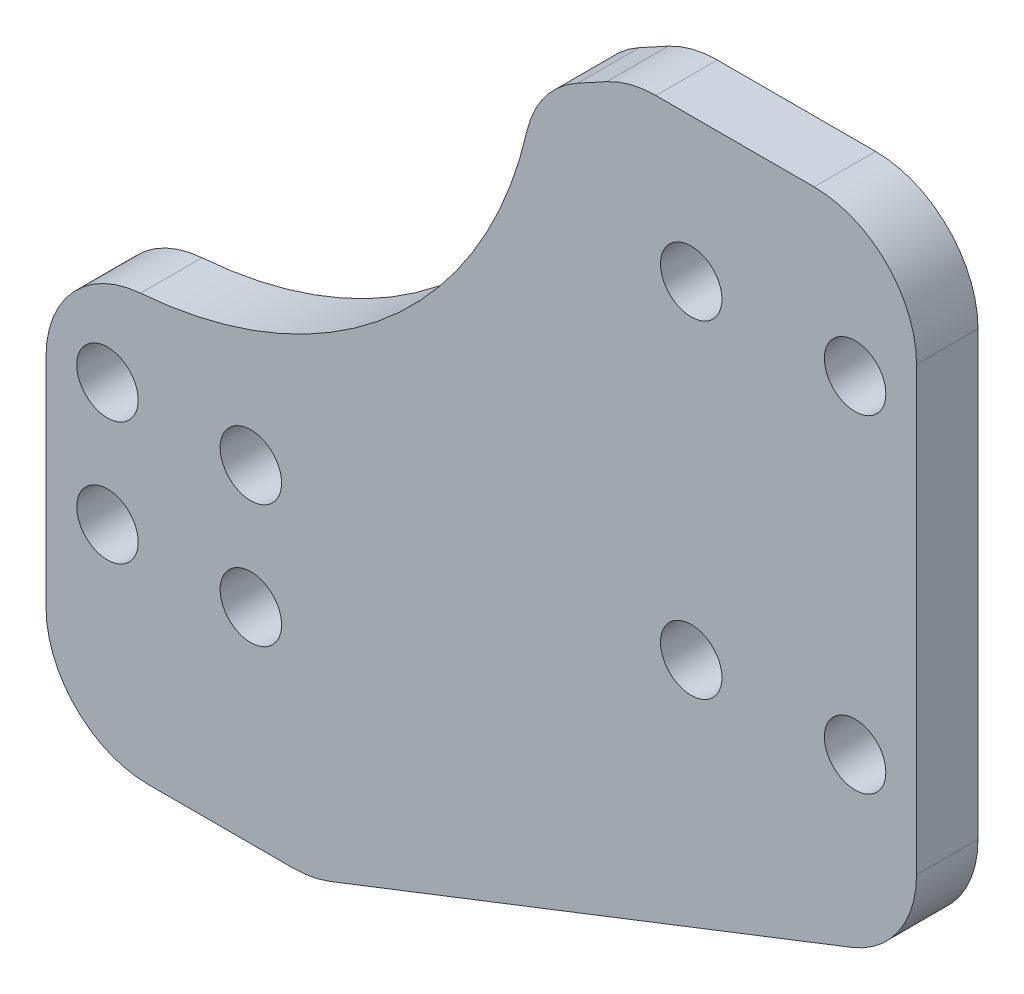
SolidWorks part; units mm, degrees
material "Thornel Mat VMA"
ref_plane "前视基准面" through (0, 0, 0) normal (0, 0, 1) x (1, 0, 0)
ref_plane "上视基准面" through (0, 0, 0) normal (0, 1, 0) x (1, 0, 0)
ref_plane "右视基准面" through (0, 0, 0) normal (1, 0, 0) x (0, 0, -1)
other "Configuration Table"
sketch "草图1" plane through (0, 0, 0) normal (0, 0, 1) x (1, 0, 0)
  line L0 (36, -1.48) -> (6.5, -13)
  line L1 (-6.5, -13) -> (6.5, -13)
  line L2 (-6.5, -13) -> (-6.5, 13)
  line L3 (-6.5, 13) -> (6.5, 13)
  line L4 (6.5, -13) -> (6.5, 13)
  line L5 (-6.5, -13) -> (6.5, 13) construction
  line L6 (-6.5, 13) -> (6.5, -13) construction
  line L7 (-3.5, -3) -> (3.5, -3) construction
  line L8 (-3.5, -3) -> (-3.5, 3) construction
  line L9 (-3.5, 3) -> (3.5, 3) construction
  line L10 (3.5, -3) -> (3.5, 3) construction
  line L11 (-3.5, -3) -> (3.5, 3) construction
  line L12 (-3.5, 3) -> (3.5, -3) construction
  line L13 (22, 28.52) -> (36, 28.52)
  line L14 (22, 28.52) -> (22, -1.48)
  line L15 (22, -1.48) -> (36, -1.48)
  line L16 (36, 28.52) -> (36, -1.48)
  line L17 (22, 28.52) -> (36, -1.48) construction
  line L18 (22, -1.48) -> (36, 28.52) construction
  line L19 (25, 5.52) -> (33, 5.52) construction
  line L20 (25, 5.52) -> (25, 21.52) construction
  line L21 (25, 21.52) -> (33, 21.52) construction
  line L22 (33, 5.52) -> (33, 21.52) construction
  line L23 (25, 5.52) -> (33, 21.52) construction
  line L24 (25, 21.52) -> (33, 5.52) construction
  line L25 (22, 28.52) -> (-6.5, 13)
  circle A0 centre (33, 21.52) radius 1.5
  circle A1 centre (33, 5.52) radius 1.5
  circle A2 centre (25, 5.52) radius 1.5
  circle A3 centre (25, 21.52) radius 1.5
  circle A4 centre (3.5, 3) radius 1.5
  circle A5 centre (3.5, -3) radius 1.5
  circle A6 centre (-3.5, -3) radius 1.5
  circle A7 centre (-3.5, 3) radius 1.5
  point P0 (0, 0)
  point P6 (0, 0)
  point P11 (29, 13.52)
  point P16 (29, 13.52)
  dimension "D1" = 3
  dimension "D9" = 10
  dimension "D10" = 3
  dimension "D2" = 8
  dimension "D3" = 29
  dimension "D4" = 13.52
  dimension "D5" = 3
  dimension "D6" = 30
  dimension "D7" = 7
  dimension "D8" = 6
  dimension "D11" = 16
extrude "凸台-拉伸1" add sketch "草图1" along normal blind 3 contours L1 L4 L3 L2 A7 A6 A5 A4 | L14 L25 L3 L4 L0 L15 | L16 L13 L14 L15 A3 A2 A1 A0
sketch "草图2" plane through (0, 0, 3) normal (0, 0, 1) x (1, 0, 0)
  line L0 (-6.5, -13) -> (-6.5, 13) construction
  line L2 (22, 28.52) -> (36, 28.52) construction
  circle A0 centre (-3.5, 28.52) radius 21
  dimension "D1" = 42
  dimension "D2" = 3
extrude "切除-拉伸1" cut sketch "草图2" against normal blind 3
fillet "圆角1" radius 5 7 edges at (-6.5, -13, 1.5) (6.5, -13, 1.5) (36, -1.48, 1.5) (36, 28.52, 1.5) (22, 28.52, 1.5) (17.3465, 25.9859, 1.5) (-6.5, 7.7354, 1.5)
sketch "草图3" plane through (0, 0, 3) normal (0, 0, 1) x (1, 0, 0)
  line L0 (33, 21.52) -> (33, 5.52) construction
  line L1 (33, 13.52) -> (37, 13.52) construction
  line L2 (38, 19.02) -> (38, 28.52)
  line L3 (38, 8.02) -> (36, 8.02)
  line L4 (38, 8.02) -> (38, 19.02)
  line L5 (38, 19.02) -> (36, 19.02)
  line L6 (-6.5, 2.597) -> (-6.5, -8)
  line L7 (-1.5, -13) -> (5.5584, -13)
  line L8 (7.3771, -12.6575) -> (32.8188, -2.7223)
  line L9 (36, 1.9352) -> (36, 23.52)
  line L10 (31, 28.52) -> (23.2731, 28.52)
  line L11 (20.8819, 27.9111) -> (19.4594, 27.1365)
  line L12 (-6.5, 2.597) -> (-6.5, -8)
  line L13 (-1.5, -13) -> (5.5584, -13)
  line L14 (7.3771, -12.6575) -> (32.8188, -2.7223)
  line L15 (36, 1.9352) -> (36, 23.52)
  line L16 (31, 28.52) -> (23.2731, 28.52)
  line L17 (20.8819, 27.9111) -> (19.4594, 27.1365)
  line L18 (36, 8.02) -> (36, 19.02)
  line L19 (38, 8.02) -> (36, 19.02) construction
  line L20 (38, 19.02) -> (36, 8.02) construction
  line L21 (38, 28.52) -> (31, 28.52)
  line L22 (38, 8.02) -> (38, -2.7223)
  line L23 (38, -2.7223) -> (32.8188, -2.7223)
  arc A8 (-6.5, -8) -> (-1.5, -13) centre (-1.5, -8) ccw
  arc A9 (5.5584, -13) -> (7.3771, -12.6575) centre (5.5584, -8) ccw
  arc A10 (32.8188, -2.7223) -> (36, 1.9352) centre (31, 1.9352) ccw
  arc A11 (36, 23.52) -> (31, 28.52) centre (31, 23.52) ccw
  arc A12 (23.2731, 28.52) -> (20.8819, 27.9111) centre (23.2731, 23.52) ccw
  arc A13 (19.4594, 27.1365) -> (16.9755, 23.8559) centre (21.8506, 22.7453) ccw
  arc A14 (-1.8846, 7.5822) -> (16.9755, 23.8559) centre (-3.5, 28.52) ccw
  arc A15 (-1.8846, 7.5822) -> (-6.5, 2.597) centre (-1.5, 2.597) ccw
  arc A16 (-6.5, -8) -> (-1.5, -13) centre (-1.5, -8) ccw
  arc A17 (5.5584, -13) -> (7.3771, -12.6575) centre (5.5584, -8) ccw
  arc A18 (32.8188, -2.7223) -> (36, 1.9352) centre (31, 1.9352) ccw
  arc A19 (36, 23.52) -> (31, 28.52) centre (31, 23.52) ccw
  arc A20 (23.2731, 28.52) -> (20.8819, 27.9111) centre (23.2731, 23.52) ccw
  arc A21 (19.4594, 27.1365) -> (16.9755, 23.8559) centre (21.8506, 22.7453) ccw
  arc A22 (-1.8846, 7.5822) -> (16.9755, 23.8559) centre (-3.5, 28.52) ccw
  arc A23 (-1.8846, 7.5822) -> (-6.5, 2.597) centre (-1.5, 2.597) ccw
  arc M20 (32.8188, -2.7223) -> (36, 1.9352) centre (31, 1.9352) ccw
  line M21 (36, 1.9352) -> (36, 23.52)
  arc M22 (36, 23.52) -> (31, 28.52) centre (31, 23.52) ccw
  dimension "D2" = 2
  dimension "D3" = 11
  dimension "D1" = 0
extrude "凸台-拉伸2" [suppressed] add sketch "草图3" against normal blind 3 contours L2 L21 L5 M22 M21 | L23 L22 L3 M21 M20
fillet "圆角2" [suppressed] radius 1
fillet "圆角3" [suppressed] radius 1
